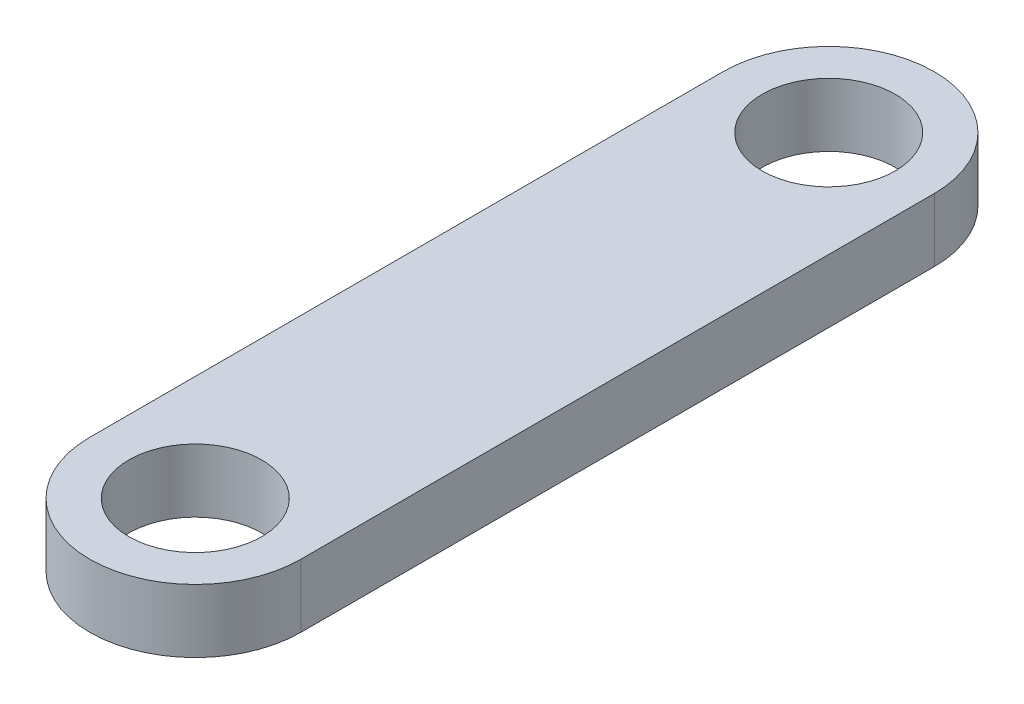
SolidWorks part; units mm, degrees
material "6061-T6 (SS)"
ref_plane "X-Y Datum" through (0, 0, 0) normal (0, 0, 1) x (1, 0, 0)
ref_plane "X-Z Datum" through (0, 0, 0) normal (0, 1, 0) x (1, 0, 0)
ref_plane "Y-Z Datum" through (0, 0, 0) normal (1, 0, 0) x (0, 0, -1)
sketch "Sketch1" plane through (0, 0, 0) normal (0, 1, 0) x (1, 0, 0)
  line L0 (3.175, -19.05) -> (3.175, 0)
  line L1 (-3.175, -19.05) -> (-3.175, 0)
  circle A0 centre (0, 0) radius 2
  circle A1 centre (0, -19.05) radius 2
  arc A2 (3.175, -19.05) -> (-3.175, -19.05) centre (0, -19.05) cw
  arc A3 (3.175, 0) -> (-3.175, 0) centre (0, 0) ccw
  dimension "D1" = 4
  dimension "D3" = 19.05
  dimension "D4" = 6.35
extrude "Boss-Extrude1" add sketch "Sketch1" against normal blind 1.905
